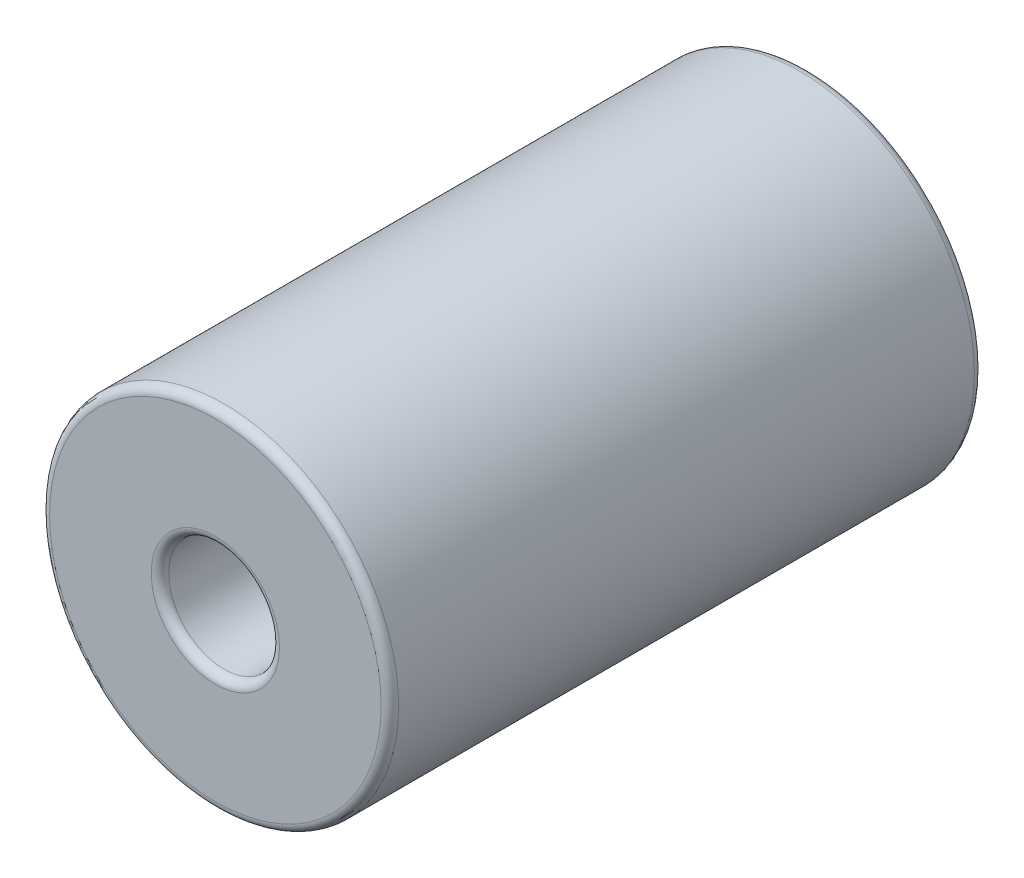
SolidWorks part; units mm, degrees
material "1060 Сплав"
ref_plane "Спереди" through (0, 0, 0) normal (0, 0, 1) x (1, 0, 0)
ref_plane "Сверху" through (0, 0, 0) normal (0, 1, 0) x (1, 0, 0)
ref_plane "Справа" through (0, 0, 0) normal (1, 0, 0) x (0, 0, -1)
sketch "Эскиз1" plane through (0, 0, 0) normal (0, 0, 1) x (1, 0, 0)
  circle A0 centre (0, 0) radius 10
extrude "Бобышка-Вытянуть1" add sketch "Эскиз1" along normal blind 34
sketch "Эскиз2" plane through (0, 0, 34) normal (0, 0, 1) x (1, 0, 0)
  circle A0 centre (0, 0) radius 3.175
extrude "Вырез-Вытянуть1" cut sketch "Эскиз2" against normal blind 11
sketch "Эскиз3" plane through (0, 0, 0) normal (0, 0, -1) x (-1, 0, 0)
  circle A0 centre (0, 0) radius 4
extrude "Вырез-Вытянуть2" cut sketch "Эскиз3" against normal blind 11
fillet "Скругление1" radius 0.5 2 edges at (10, 0, 0) (10, 0, 34)
fillet "Скругление2" radius 0.5 2 edges at (3.175, 0, 34) (-4, 0, 0)
fillet "Скругление3" radius 0.5 2 edges at (3.175, 0, 23) (-4, 0, 11)
